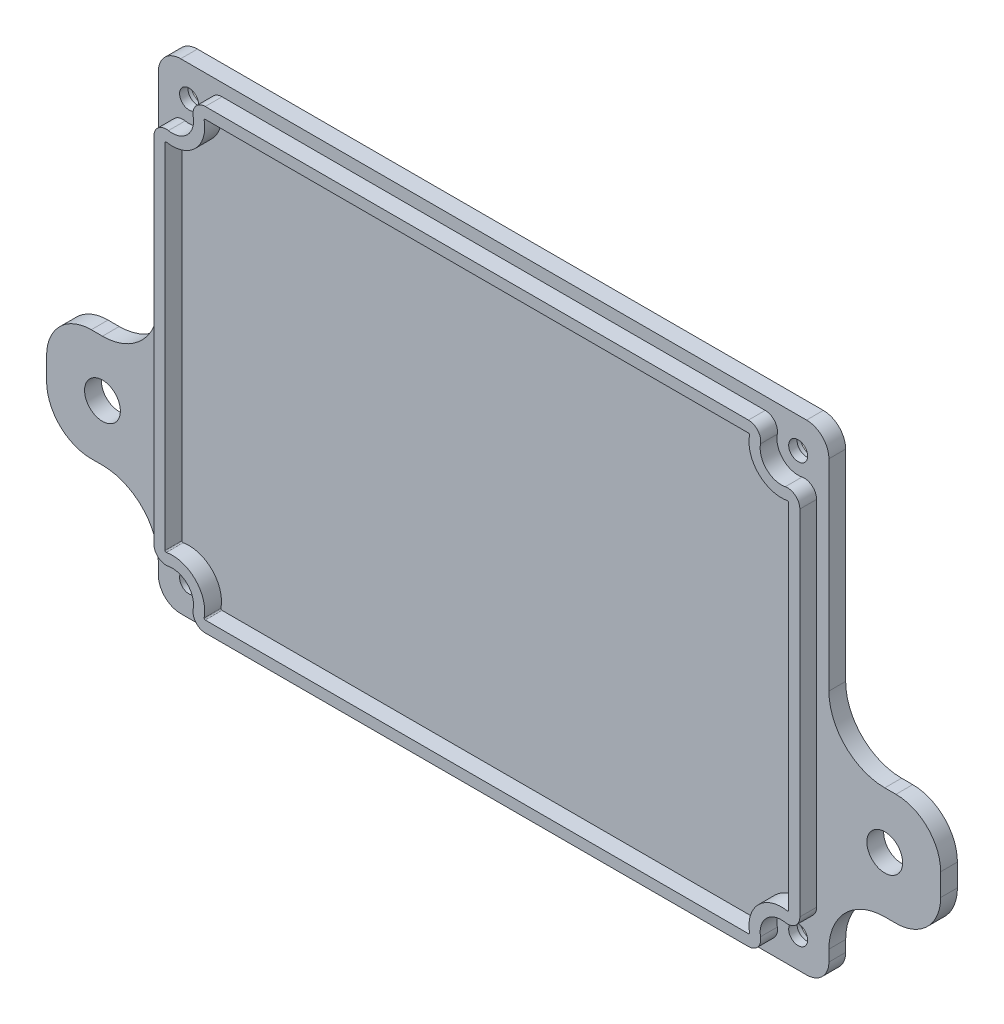
SolidWorks part; units mm, degrees
ref_plane "Front Plane" through (0, 0, 0) normal (0, 0, 1) x (1, 0, 0)
ref_plane "Top Plane" through (0, 0, 0) normal (0, 1, 0) x (1, 0, 0)
ref_plane "Right Plane" through (0, 0, 0) normal (1, 0, 0) x (0, 0, -1)
sketch "Sketch1" plane through (0, 0, 0) normal (0, 0, 1) x (1, 0, 0)
  line L0 (-60, 0) -> (60, 0) construction
  line L1 (-56, -43) -> (56, -43)
  line L2 (-60, -39) -> (-60, 39)
  line L3 (-56, 43) -> (56, 43)
  line L4 (60, -39) -> (60, 39)
  line L5 (-60, -43) -> (60, 43) construction
  line L6 (-60, 43) -> (60, -43) construction
  line L7 (0, 43) -> (0, -43) construction
  arc A0 (-56, -43) -> (-60, -39) centre (-56, -39) cw
  arc A1 (56, -43) -> (60, -39) centre (56, -39) ccw
  arc A2 (56, 43) -> (60, 39) centre (56, 39) cw
  arc A3 (-60, 39) -> (-56, 43) centre (-56, 39) cw
  circle A4 centre (-54.5, 37.5) radius 1.7
  circle A5 centre (-54.5, -37.5) radius 1.7
  circle A6 centre (54.5, -37.5) radius 1.7
  circle A7 centre (54.5, 37.5) radius 1.7
  point P0 (0, 0)
  dimension "D1" = 4
  dimension "D2" = 37.5
  dimension "D3" = 54.5
  dimension "D4" = 120
  dimension "D5" = 86
extrude "Boss-Extrude1" add sketch "Sketch1" along normal blind 3
sketch "Sketch2" plane through (0, 0, 3) normal (0, 0, 1) x (1, 0, 0)
  line L0 (-57.8, 31.6017) -> (-57.8, -31.6017)
  line L1 (-48.6017, 40.8) -> (48.6017, 40.8)
  line L2 (0, 43) -> (0, -43) construction
  line L3 (56, 43) -> (-56, 43) construction
  line L4 (-56, -43) -> (56, -43) construction
  line L5 (-60, 0) -> (60, 0) construction
  line L6 (-60, 39) -> (-60, -39) construction
  line L7 (60, -39) -> (60, 39) construction
  line L8 (-48.6017, -40.8) -> (48.6017, -40.8)
  line L9 (57.8, 31.6017) -> (57.8, -31.6017)
  line L10 (-48.6017, 38.8) -> (48.6017, 38.8)
  line L11 (55.8, 31.6017) -> (55.8, -31.6017)
  line L12 (-48.6017, -38.8) -> (48.6017, -38.8)
  line L13 (-55.8, 31.6017) -> (-55.8, -31.6017)
  arc A0 (-55.1967, 33.7644) -> (-50.7644, 38.1967) centre (-54.5, 37.5) ccw
  arc A1 (50.7644, 38.1967) -> (55.1967, 33.7644) centre (54.5, 37.5) ccw
  arc A3 (-50.7644, -38.1967) -> (-55.1967, -33.7644) centre (-54.5, -37.5) ccw
  arc A4 (55.1967, -33.7644) -> (50.7644, -38.1967) centre (54.5, -37.5) ccw
  arc A5 (-48.6017, -40.8) -> (-50.7644, -38.1967) centre (-48.6017, -38.6) cw
  arc A6 (-57.8, -31.6017) -> (-55.1967, -33.7644) centre (-55.6, -31.6017) ccw
  arc A7 (57.8, -31.6017) -> (55.1967, -33.7644) centre (55.6, -31.6017) cw
  arc A8 (48.6017, 40.8) -> (50.7644, 38.1967) centre (48.6017, 38.6) cw
  arc A9 (57.8, 31.6017) -> (55.1967, 33.7644) centre (55.6, 31.6017) ccw
  arc A10 (-57.8, 31.6017) -> (-55.1967, 33.7644) centre (-55.6, 31.6017) cw
  arc A11 (-48.6017, 40.8) -> (-50.7644, 38.1967) centre (-48.6017, 38.6) ccw
  arc A12 (50.7644, -38.1967) -> (48.6017, -40.8) centre (48.6017, -38.6) cw
  arc A13 (48.6017, 38.8) -> (48.7983, 38.5633) centre (48.6017, 38.6) cw
  arc A14 (48.7983, 38.5633) -> (55.5633, 31.7983) centre (54.5, 37.5) ccw
  arc A15 (55.8, 31.6017) -> (55.5633, 31.7983) centre (55.6, 31.6017) ccw
  arc A16 (55.8, -31.6017) -> (55.5633, -31.7983) centre (55.6, -31.6017) cw
  arc A17 (55.5633, -31.7983) -> (48.7983, -38.5633) centre (54.5, -37.5) ccw
  arc A18 (48.7983, -38.5633) -> (48.6017, -38.8) centre (48.6017, -38.6) cw
  arc A19 (-48.6017, -38.8) -> (-48.7983, -38.5633) centre (-48.6017, -38.6) cw
  arc A20 (-48.7983, -38.5633) -> (-55.5633, -31.7983) centre (-54.5, -37.5) ccw
  arc A21 (-55.8, -31.6017) -> (-55.5633, -31.7983) centre (-55.6, -31.6017) ccw
  arc A22 (-55.8, 31.6017) -> (-55.5633, 31.7983) centre (-55.6, 31.6017) cw
  arc A23 (-55.5633, 31.7983) -> (-48.7983, 38.5633) centre (-54.5, 37.5) ccw
  arc A24 (-48.6017, 38.8) -> (-48.7983, 38.5633) centre (-48.6017, 38.6) ccw
  point P10 (-52.6159, -40.8)
  point P34 (-57.8, -35.6159)
  point P37 (57.8, -35.6159)
  point P40 (52.6159, 40.8)
  point P43 (57.8, 35.6159)
  point P46 (-57.8, 35.6159)
  point P49 (-52.6159, 40.8)
  point P52 (52.6159, -40.8)
  dimension "D1" = 7.6
  dimension "D4" = 2.2
  dimension "D5" = 2.2
  dimension "D2" = 2.2
  dimension "D3" = 2.2
  dimension "D6" = 2
extrude "Boss-Extrude2" add sketch "Sketch2" along normal blind 3
sketch "Sketch3" plane through (0, 0, 3) normal (0, 0, 1) x (1, 0, 0)
  line L0 (60, 3) -> (60, -7)
  line L5 (0, 38.8) -> (0, -38.8) construction
  line L6 (48.6017, 38.8) -> (-48.6017, 38.8) construction
  line L7 (-48.6017, -38.8) -> (48.6017, -38.8) construction
  line L8 (60, -27) -> (60, -37)
  line L9 (60, -39) -> (60, 39) construction
  line L10 (70, -7) -> (72, -7)
  line L11 (60, -7) -> (60, -27)
  line L12 (70, -27) -> (72, -27)
  line L13 (80, -15) -> (80, -19)
  line L14 (56, 43) -> (-56, 43) construction
  line L15 (-70, -7) -> (-72, -7)
  line L16 (-80, -15) -> (-80, -19)
  line L17 (70, -7) -> (70, -27) construction
  line L18 (-70, -27) -> (-72, -27)
  line L19 (-60, -27) -> (-60, -37)
  line L20 (-60, 3) -> (-60, -7)
  line L21 (-60, -7) -> (-60, -27)
  arc A2 (72, -27) -> (80, -19) centre (72, -19) ccw
  arc A3 (72, -7) -> (80, -15) centre (72, -15) cw
  arc A4 (60, 3) -> (70, -7) centre (70, 3) ccw
  arc A5 (60, -37) -> (70, -27) centre (70, -37) cw
  circle A6 centre (70, -17) radius 3.2
  circle A7 centre (-70, -17) radius 3.2
  arc A8 (-60, 3) -> (-70, -7) centre (-70, 3) cw
  arc A9 (-72, -7) -> (-80, -15) centre (-72, -15) ccw
  arc A10 (-72, -27) -> (-80, -19) centre (-72, -19) cw
  arc A11 (-60, -37) -> (-70, -27) centre (-70, -37) ccw
  point P16 (80, -7)
  dimension "D3" = 20
  dimension "D2" = 8
  dimension "D5" = 10
  dimension "D6" = 10
  dimension "D1" = 20
  dimension "D4" = 50
extrude "Boss-Extrude3" add sketch "Sketch3" against normal up to surface (3 mm away) up to face at (56.2, -37.5, 0)
sketch "Sketch4" plane through (0, 0, 0) normal (0, 0, -1) x (-1, 0, 0)
  circle A0 centre (-54.5, 37.5) radius 2.85
  circle A1 centre (54.5, 37.5) radius 2.85
  circle A2 centre (54.5, -37.5) radius 2.85
  circle A3 centre (-54.5, -37.5) radius 2.85
  circle A4 centre (-54.5, -37.5) radius 1.7 construction
  circle A5 centre (54.5, -37.5) radius 1.7 construction
  circle A6 centre (54.5, 37.5) radius 1.7 construction
  circle A7 centre (-54.5, 37.5) radius 1.7 construction
  circle A8 centre (-54.5, -37.5) radius 1.7
  circle A9 centre (54.5, -37.5) radius 1.7
  circle A10 centre (54.5, 37.5) radius 1.7
  circle A11 centre (-54.5, 37.5) radius 1.7
  dimension "D1" = 5.7
extrude "Cut-Extrude1" cut sketch "Sketch4" against normal blind 1.5
